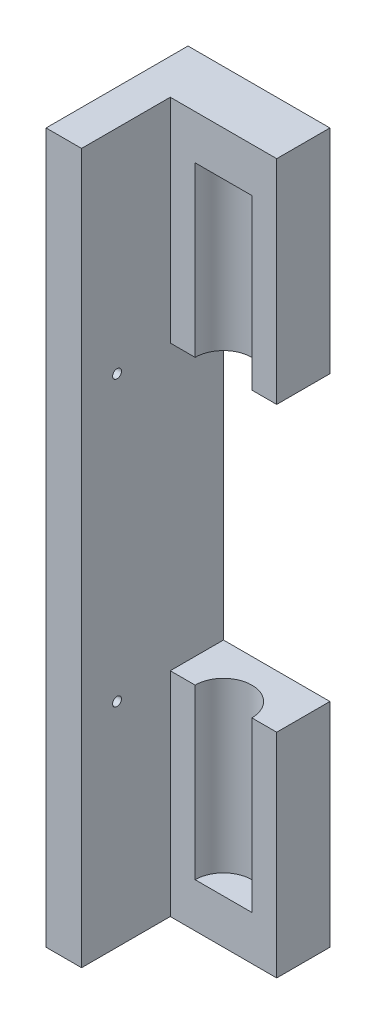
SolidWorks part; units mm, degrees
material "ABS PC"
ref_plane "前视基准面" through (0, 0, 0) normal (0, 0, 1) x (1, 0, 0)
ref_plane "上视基准面" through (0, 0, 0) normal (0, 1, 0) x (1, 0, 0)
ref_plane "右视基准面" through (0, 0, 0) normal (1, 0, 0) x (0, 0, -1)
sketch "草图1" plane through (0, 0, 0) normal (0, 1, 0) x (1, 0, 0)
  line L0 (0, 0) -> (0, -25)
  line L5 (0, -25) -> (-10, -25)
  line L6 (-10, -25) -> (-10, 15)
  line L7 (-10, 15) -> (30, 15)
  line L8 (30, 15) -> (30, 0)
  line L9 (30, 0) -> (0, 0)
  point P0 (0, 0)
  dimension "D1" = 40
  dimension "D2" = 15
  dimension "D3" = 40
  dimension "D4" = 10
extrude "凸台-拉伸2" add sketch "草图1" along normal blind 200
ref_plane "基准面1" through (0, 187.5, 0) normal (0, 1, 0) x (1, 0, 0)
sketch "草图3" plane through (0, 187.5, 0) normal (0, 1, 0) x (1, 0, 0)
  line L0 (0, 0) -> (30, 0) construction
  circle A0 centre (15, 0) radius 8
  dimension "D1" = 15
extrude "切除-拉伸1" cut sketch "草图3" against normal blind 175
ref_plane "基准面2" through (0, 140, 0) normal (0, 1, 0) x (1, 0, 0)
sketch "草图4" plane through (0, 140, 0) normal (0, 1, 0) x (1, 0, 0)
  line L0 (0, 0) -> (0, 15)
  line L1 (30, 15) -> (-10, 15) construction
  line L2 (0, 15) -> (30, 15)
  line L3 (30, 15) -> (30, 0)
  line L4 (30, 0) -> (0, 0)
extrude "切除-拉伸2" cut sketch "草图4" against normal blind 80
hole_wizard "M3 螺纹孔1" positions "草图5" profile "草图6" tap size "M3" standard "GB" end condition through all
sketch "草图5" plane through (0, 0, 0) normal (1, 0, 0) x (0, 0, -1)
  line L0 (22, 140) -> (-22, 140) construction
  line L1 (-25, 200) -> (-25, 0) construction
  point P0 (-15, 140)
  point P7 (-15, 60)
  dimension "D1" = 10
  dimension "D2" = 80
sketch "草图6" plane through (0, 140, 15) normal (0, 1, 0) x (0, 0, -1)
  line L0 (0, 0) -> (0, 10)
  line L1 (0, 10) -> (1.25, 10)
  line L2 (1.25, 10) -> (1.25, 0)
  line L5 (1.25, 0) -> (0, 0)
  line L11 (0, -6.35) -> (0, 107.95) construction
  dimension "通孔螺纹孔钻头直径" = 2.5
  dimension "通孔螺纹孔钻头深度" = 10
cosmetic thread "孔螺蚊线1" parameters "D2"=3
cosmetic thread "孔螺蚊线2" parameters "D2"=3
